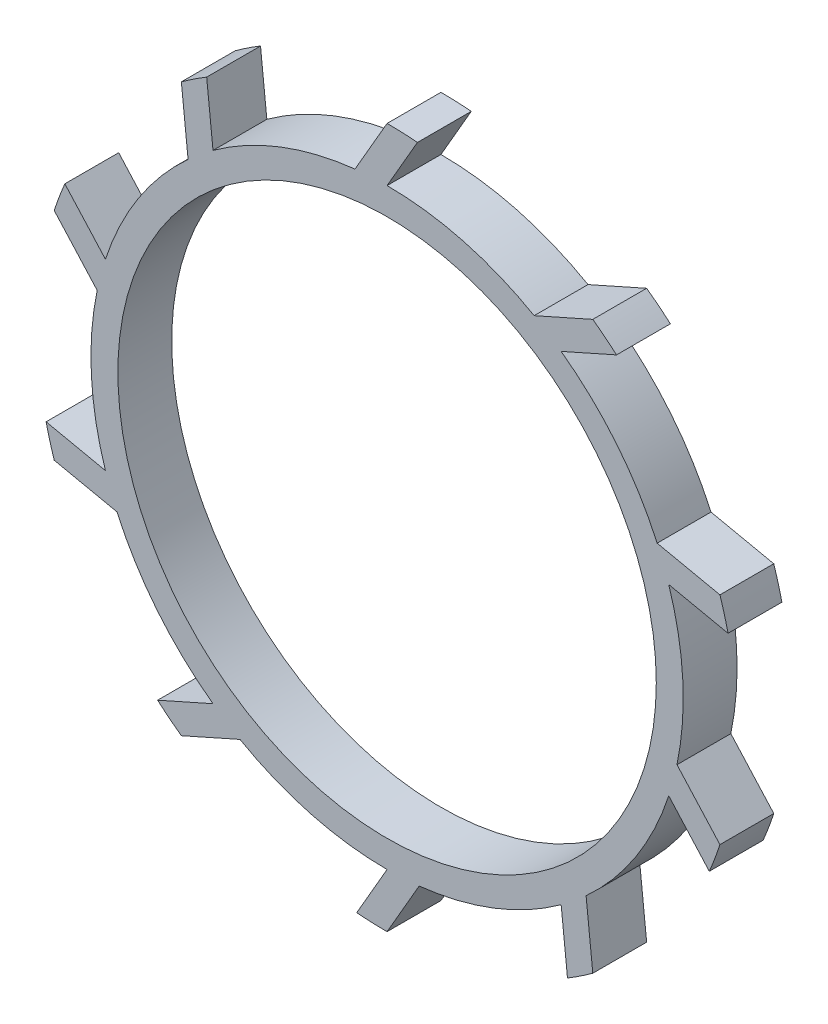
SolidWorks part; units mm, degrees
ref_plane "Front Plane" through (0, 0, 0) normal (0, 0, 1) x (1, 0, 0)
ref_plane "Top Plane" through (0, 0, 0) normal (0, 1, 0) x (1, 0, 0)
ref_plane "Right Plane" through (0, 0, 0) normal (1, 0, 0) x (0, 0, -1)
sketch "Sketch1" plane through (0, 0, 0) normal (0, 0, 1) x (1, 0, 0)
  line L0 (0, -1000) -> (0, 49000) construction
  line L1 (0, 32.5) -> (-2.9803, 27.338)
  line L2 (0, 27.5) -> (2.8162, 32.3778)
  line L3 (19.103, 26.2931) -> (13.6578, 23.8687)
  line L4 (16.1641, 22.248) -> (21.3095, 24.5389)
  line L5 (30.9093, 10.0431) -> (25.0791, 11.2823)
  line L6 (26.1541, 8.498) -> (31.6633, 7.3269)
  line L7 (30.9093, -10.0431) -> (26.921, -5.6135)
  line L8 (26.1541, -8.498) -> (29.9228, -12.6836)
  line L9 (19.103, -26.2931) -> (18.48, -20.3652)
  line L10 (16.1641, -22.248) -> (16.7528, -27.8495)
  line L11 (0, -32.5) -> (2.9803, -27.338)
  line L12 (0, -27.5) -> (-2.8162, -32.3778)
  line L13 (-19.103, -26.2931) -> (-13.6578, -23.8687)
  line L14 (-16.1641, -22.248) -> (-21.3095, -24.5389)
  line L15 (-30.9093, -10.0431) -> (-25.0791, -11.2823)
  line L16 (-26.1541, -8.498) -> (-31.6633, -7.3269)
  line L17 (-30.9093, 10.0431) -> (-26.921, 5.6135)
  line L18 (-26.1541, 8.498) -> (-29.9228, 12.6836)
  line L19 (-19.103, 26.2931) -> (-18.48, 20.3652)
  line L20 (-16.1641, 22.248) -> (-16.7528, 27.8495)
  circle A0 centre (0, 0) radius 25
  arc A1 (-2.9803, 27.338) -> (-16.1641, 22.248) centre (0, 0) ccw
  arc A2 (-16.7528, 27.8495) -> (-19.103, 26.2931) centre (0, 0) ccw
  arc A3 (-18.48, 20.3652) -> (-26.1541, 8.498) centre (0, 0) ccw
  arc A4 (2.8162, 32.3778) -> (0, 32.5) centre (0, 0) ccw
  arc A5 (13.6578, 23.8687) -> (0, 27.5) centre (0, 0) ccw
  arc A6 (21.3095, 24.5389) -> (19.103, 26.2931) centre (0, 0) ccw
  arc A7 (25.0791, 11.2823) -> (16.1641, 22.248) centre (0, 0) ccw
  arc A8 (31.6633, 7.3269) -> (30.9093, 10.0431) centre (0, 0) ccw
  arc A9 (26.921, -5.6135) -> (26.1541, 8.498) centre (0, 0) ccw
  arc A10 (29.9228, -12.6836) -> (30.9093, -10.0431) centre (0, 0) ccw
  arc A11 (18.48, -20.3652) -> (26.1541, -8.498) centre (0, 0) ccw
  arc A12 (16.7528, -27.8495) -> (19.103, -26.2931) centre (0, 0) ccw
  arc A13 (2.9803, -27.338) -> (16.1641, -22.248) centre (0, 0) ccw
  arc A14 (-2.8162, -32.3778) -> (0, -32.5) centre (0, 0) ccw
  arc A15 (-13.6578, -23.8687) -> (0, -27.5) centre (0, 0) ccw
  arc A16 (-21.3095, -24.5389) -> (-19.103, -26.2931) centre (0, 0) ccw
  arc A17 (-25.0791, -11.2823) -> (-16.1641, -22.248) centre (0, 0) ccw
  arc A18 (-31.6633, -7.3269) -> (-30.9093, -10.0431) centre (0, 0) ccw
  arc A19 (-26.921, 5.6135) -> (-26.1541, -8.498) centre (0, 0) ccw
  arc A20 (-29.9228, 12.6836) -> (-30.9093, 10.0431) centre (0, 0) ccw
  point P50 (0, 0)
  dimension "D1" = 50
  dimension "D2" = 55
  dimension "D3" = 65
  dimension "D4" = 30
  dimension "D5" = 10
extrude "Boss-Extrude1" add sketch "Sketch1" along normal mid plane 5
scale "Scale1" scale about centroid uniform scaling yes scale factor 1.5
